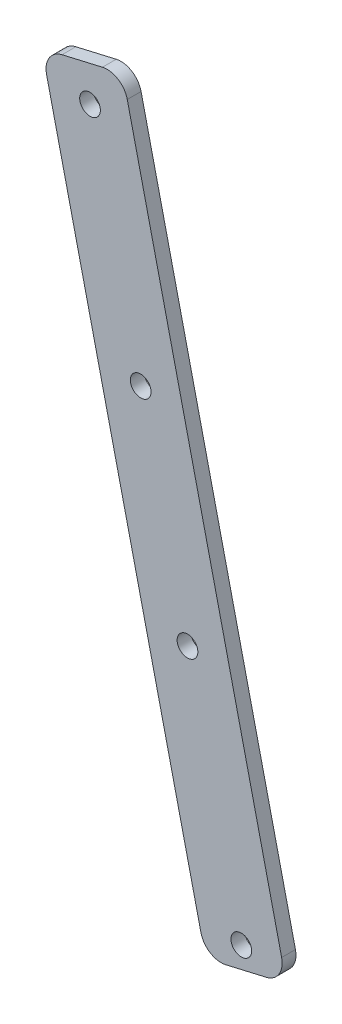
SolidWorks part; units mm, degrees
ref_plane "前视基准面" through (0, 0, 0) normal (0, 0, 1) x (1, 0, 0)
ref_plane "上视基准面" through (0, 0, 0) normal (0, 1, 0) x (1, 0, 0)
ref_plane "右视基准面" through (0, 0, 0) normal (1, 0, 0) x (0, 0, -1)
sketch "草图1" plane through (0, 0, 0) normal (0, 0, 1) x (1, 0, 0)
  line L4 (-13.6362, 32.2538) -> (8.7211, -64.1887)
  line L5 (12.3211, -66.4337) -> (18.1661, -65.0787)
  line L6 (20.4111, -61.4788) -> (-1.9462, 34.9637)
  line L7 (-5.5462, 37.2087) -> (-11.3912, 35.8538)
  line L8 (-13.6362, 32.2538) -> (8.7211, -64.1887)
  line L9 (12.3211, -66.4337) -> (18.1661, -65.0787)
  line L10 (20.4111, -61.4788) -> (-1.9462, 34.9637)
  line L11 (-5.5462, 37.2087) -> (-11.3912, 35.8538)
  circle A0 centre (-7.3395, 31.6604) radius 1.5 construction
  circle A1 centre (0, 0) radius 1.5 construction
  circle A2 centre (6.7749, -29.225) radius 1.5 construction
  circle A3 centre (14.5661, -62.8337) radius 1.5 construction
  circle A12 centre (-7.3395, 31.6604) radius 1.5
  circle A13 centre (0, 0) radius 1.5
  circle A14 centre (6.7749, -29.225) radius 1.5
  circle A15 centre (14.5661, -62.8337) radius 1.5
  arc A20 (8.7211, -64.1887) -> (12.3211, -66.4337) centre (11.6436, -63.5112) ccw
  arc A21 (8.7211, -64.1887) -> (12.3211, -66.4337) centre (11.6436, -63.5112) ccw
  arc A22 (18.1661, -65.0787) -> (20.4111, -61.4788) centre (17.4886, -62.1562) ccw
  arc A23 (18.1661, -65.0787) -> (20.4111, -61.4788) centre (17.4886, -62.1562) ccw
  arc A24 (-1.9462, 34.9637) -> (-5.5462, 37.2087) centre (-4.8687, 34.2862) ccw
  arc A25 (-1.9462, 34.9637) -> (-5.5462, 37.2087) centre (-4.8687, 34.2862) ccw
  arc A26 (-11.3912, 35.8538) -> (-13.6362, 32.2538) centre (-10.7137, 32.9313) ccw
  arc A27 (-11.3912, 35.8538) -> (-13.6362, 32.2538) centre (-10.7137, 32.9313) ccw
  dimension "D1" = 0
extrude "凸台-拉伸1" add sketch "草图1" along normal blind 2
